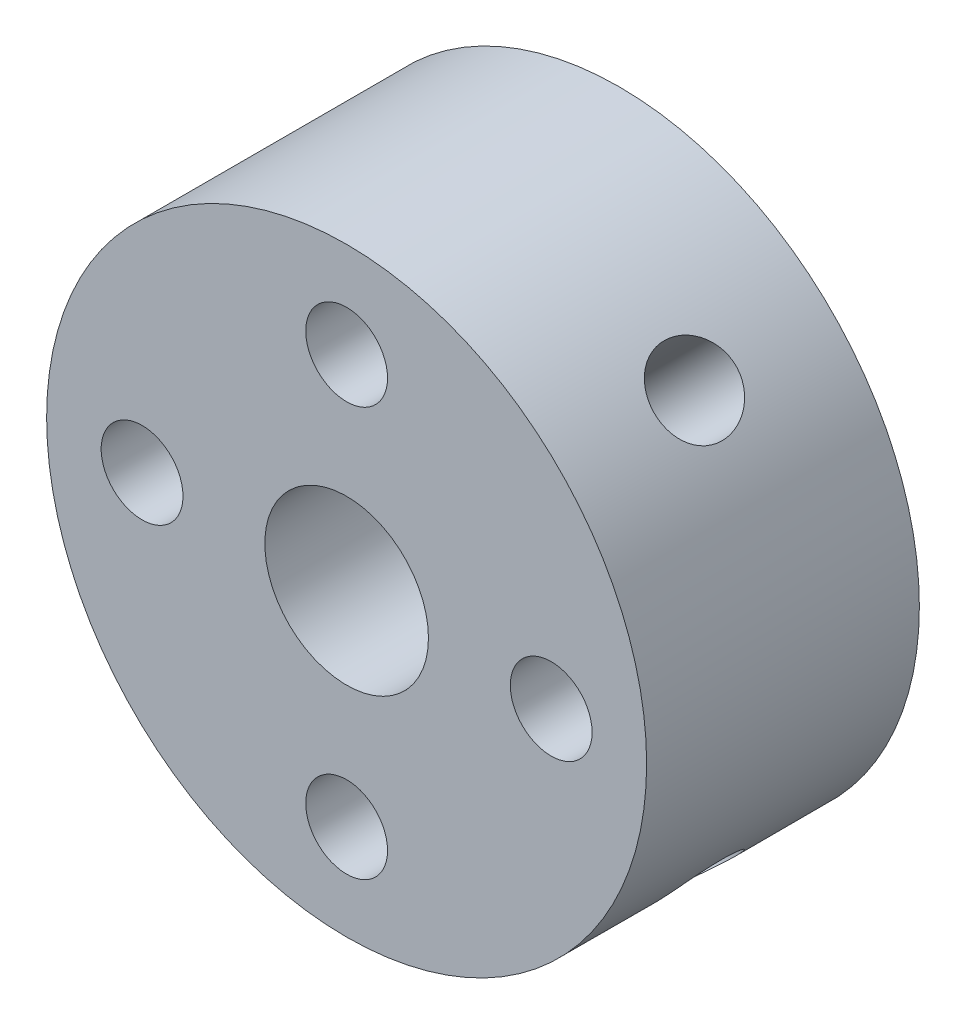
SolidWorks part; units mm, degrees
ref_plane "正面" through (0, 0, 0) normal (0, 0, 1) x (1, 0, 0)
ref_plane "平面" through (0, 0, 0) normal (0, 1, 0) x (1, 0, 0)
ref_plane "右側面" through (0, 0, 0) normal (1, 0, 0) x (0, 0, -1)
sketch "ｽｹｯﾁ1" plane through (0, 0, 0) normal (0, 0, 1) x (1, 0, 0)
  line L0 (-7.5, 0) -> (0, 0) construction
  line L1 (0, 0) -> (7.5, 0) construction
  line L2 (0, 7.5) -> (0, -7.5) construction
  circle A0 centre (0, 0) radius 11
  circle A1 centre (0, 0) radius 3
  circle A2 centre (-7.5, 0) radius 1.5
  circle A3 centre (7.5, 0) radius 1.5
  circle A4 centre (0, 7.5) radius 1.5
  circle A5 centre (0, -7.5) radius 1.5
  dimension "D1" = 6
  dimension "D2" = 22
  dimension "D3" = 3
  dimension "D5" = 15
  dimension "D4" = 15
extrude "ﾎﾞｽ - 押し出し1" add sketch "ｽｹｯﾁ1" along normal blind 10
ref_plane "平面1" through (0, 0, 0) normal (0.7071, 0.7071, 0) x (0.7071, -0.7071, 0)
ref_plane "平面2" through (0, 0, 0) normal (-0.7071, 0.7071, 0) x (0.7071, 0.7071, 0)
sketch "ｽｹｯﾁ2" plane through (0, 0, 0) normal (0.7071, 0.7071, 0) x (0.7071, -0.7071, 0)
  line L0 (0, 55) -> (0, -55) construction
  line L1 (3, 0) -> (-3, 0) construction
  circle A0 centre (0, -5) radius 1.5
  dimension "D1" = 5
  dimension "D2" = 3
extrude "ｶｯﾄ - 押し出し1" cut sketch "ｽｹｯﾁ2" along normal up to next
sketch "ｽｹｯﾁ3" plane through (0, 0, 0) normal (-0.7071, 0.7071, 0) x (0.7071, 0.7071, 0)
  line L0 (0, -55) -> (0, 55) construction
  line L1 (3, 0) -> (-3, 0) construction
  circle A0 centre (0, -5) radius 1.5
  dimension "D1" = 3
  dimension "D2" = 5
extrude "ｶｯﾄ - 押し出し2" cut sketch "ｽｹｯﾁ3" against normal up to next
